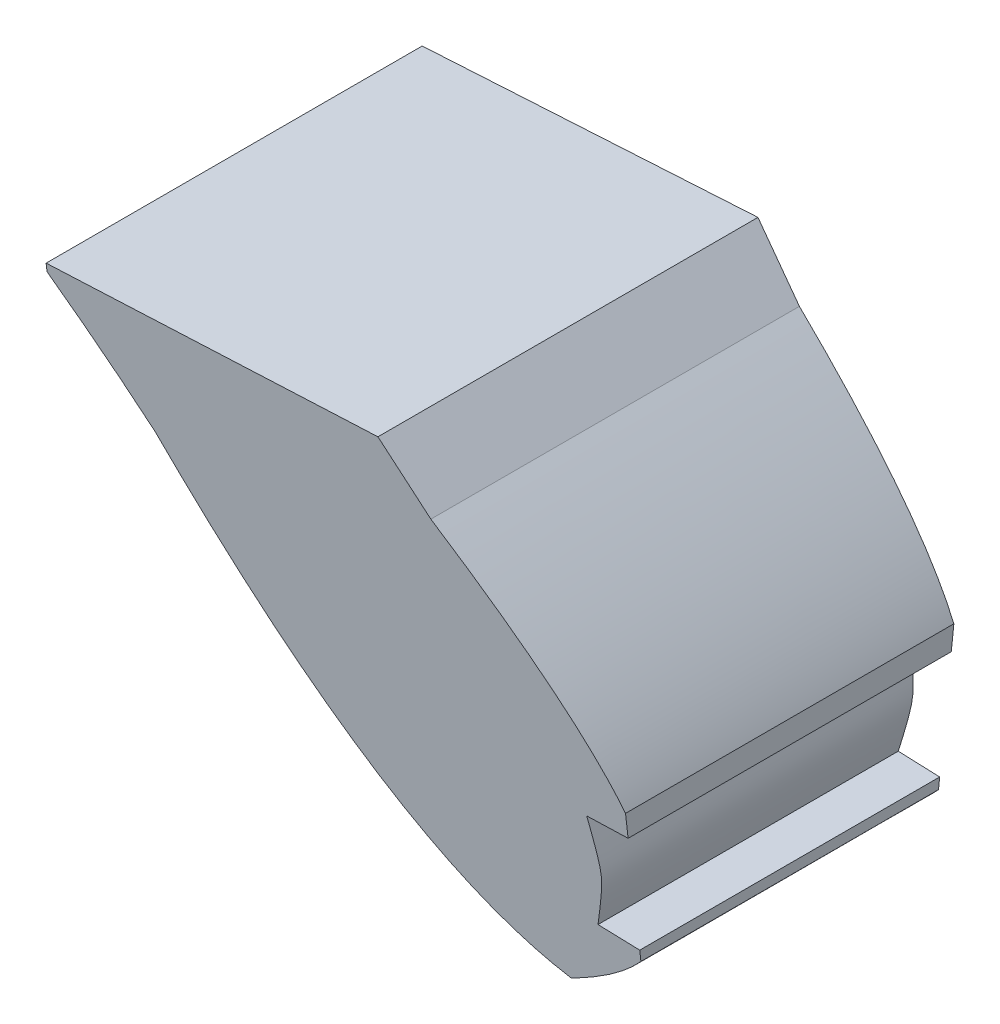
SolidWorks part; units mm, degrees
ref_plane "Alzado" through (0, 0, 0) normal (0, 0, 1) x (1, 0, 0)
ref_plane "Planta" through (0, 0, 0) normal (0, 1, 0) x (1, 0, 0)
ref_plane "Vista lateral" through (0, 0, 0) normal (1, 0, 0) x (0, 0, -1)
sketch "Croquis1" plane through (0, 0, 0) normal (0, 0, 1) x (1, 0, 0)
  line L0 (-8.9818, 12.6082) -> (-23.0359, 11.8716) construction
  line L1 (-8.9818, 12.6082) -> (-23.0359, 11.8716)
  line L2 (-8.9818, 12.6082) -> (-23.0359, 11.8716) construction
  line L4 (-8.9818, 12.6082) -> (-23.0359, 11.8716)
  line L6 (-1.3949, 1.9763) -> (0.3551, 2.2848) construction
  line L7 (-1.3949, 1.9763) -> (0.3551, 2.2848)
  line L8 (0.3551, 2.2848) -> (0.3551, 2.8423) construction
  line L9 (0.3551, 2.2848) -> (0.3551, 3.0015)
  line L10 (0.3551, -2.2848) -> (-1.3949, -2.2237) construction
  line L11 (0.3551, -2.2848) -> (-1.3949, -2.2237)
  line L12 (0.3551, 2.2848) -> (0.3551, -2.2848) construction
  line L13 (0.3551, -2.2848) -> (0.3551, -2.7233)
  line L14 (-8.9818, 12.6082) -> (-6.9949, 10.4774)
  line L15 (-23.0359, 11.5401) -> (-23.0359, 11.8716) construction
  line L16 (-23.0359, 11.5401) -> (-23.0359, 11.8716)
  arc A0 (-18.9452, 7.5409) -> (-23.0359, 11.5401) centre (-69.8841, -40.4718) ccw construction
  arc A1 (-18.9452, 7.5409) -> (-23.0359, 11.5401) centre (-69.8841, -40.4718) ccw
  spline S1 degree 2 poles (-1165.1036, 5893.6598) (818.9524, -5942.9252) (-471.5876, 5971.4584) knots 0.453698 0.453698 0.453698 0.546233 0.546233 0.546233 weights 1 1 1 only from (-18.9452, 7.5409) to (-2.8466, -5.0591) construction
  spline S2 degree 2 poles (-18.9452, 7.5409) (-10.215, -3.6976) (-2.8466, -5.0591) knots 0.497667 0.497667 0.497667 0.499554 0.499554 0.499554 weights 1 1 1
  spline S3 degree 2 poles (-5694.9897, 1886.3291) (5642.0208, -2053.6219) (-5584.6926, 2218.951) knots 0.453717 0.453717 0.453717 0.546322 0.546322 0.546322 weights 1 1 1 only from (0.3551, 3.0015) to (-6.9949, 10.4774) construction
  spline S4 degree 2 poles (0.3551, 3.0015) (-1.4487, 6.0584) (-6.9949, 10.4774) knots 0.500821 0.500821 0.500821 0.502013 0.502013 0.502013 weights 1 1 1
  spline S5 degree 2 poles (-1.3949, -2.2237) (-0.9075, -0.1237) (-1.3949, 1.9763) knots 0 0 0 1 1 1 weights 1 3.231801 1 construction
  spline S6 degree 2 poles (-1.3949, -2.2237) (-0.9075, -0.1237) (-1.3949, 1.9763) knots 0 0 0 1 1 1 weights 1 3.231801 1
  spline S7 degree 2 poles (-5992.358, 322.5754) (5976.1778, -523.0129) (-5953.8534, 722.2524) knots 0.453712 0.453712 0.453712 0.546274 0.546274 0.546274 weights 1 1 1 only from (-2.8466, -5.0591) to (0.3551, -2.7233) construction
  spline S8 degree 2 poles (-2.8466, -5.0591) (-0.7424, -3.9352) (0.3551, -2.7233) knots 0.498812 0.498812 0.498812 0.499413 0.499413 0.499413 weights 1 1 1
extrude "Saliente-Extruir1" add sketch "Croquis1" along normal mid plane 16 contours S2 S8 L13 L11 S6 L7 L9 S4 L14 L1 L16 A1
sketch "Croquis3" plane through (0, 0, 0) normal (0, 0, 1) x (1, 0, 0)
  line L0 (-6.742, 0) -> (0, 0) construction
  line L1 (-1.8181, 2) -> (-1.7771, 2.0103) construction
  line L3 (-1.8181, 2) -> (-0.1689, 2.4155) construction
  line L4 (-1.8181, 2) -> (0.3551, 3.0015)
  line L5 (0.3551, 3.0015) -> (0.3551, 0)
  line L6 (-1.9135, -2.1825) -> (0.3551, -2.2848)
  line L7 (0.3551, -2.2848) -> (0.3551, 0)
  parabola Q0 (-1.9135, -2.1825) -> (-1.8181, 2) focus (-3.3181, 0) apex (-1.3181, 0)
  dimension "D1" = 2
  dimension "D2" = 2
extrude "Cortar-Extruir1" [suppressed] cut sketch "Croquis3" against normal through all both and the other way through all
sketch "Croquis4" plane through (0, 0, 0) normal (0, 0, 1) x (1, 0, 0)
  line L0 (-1.3949, 1.9763) -> (0.3551, 2.2848) construction
  line L1 (-1.3949, 1.9763) -> (0.3551, 2.2848)
  line L2 (0.3551, 2.2848) -> (0.3551, 3.0015) construction
  line L3 (0.3551, 2.0374) -> (0.3551, 2.2848)
  line L4 (-1.3949, 1.9763) -> (0.3551, 2.0374)
  line L5 (0, 0) -> (-3.4665, 0) construction
  dimension "D1" = 2
extrude "Saliente-Extruir2" add sketch "Croquis4" along normal through all and the other way through all
sketch "Croquis7" plane through (0, 0, 0) normal (0, 0, 1) x (1, 0, 0)
  line L0 (0, 0) -> (-15.3945, 3.3171) construction
  line L1 (-17.3963, 18.9371) -> (-15.3945, 3.3171) construction
  line L2 (-15.3945, 3.3171) -> (-9.9316, -2.6296) construction
  line L3 (-15.3945, 3.3171) -> (-10.2385, 8.0535) construction
  line L4 (-17.3963, 18.9371) -> (-16.5429, 12.2783) construction
  line L5 (0, 0) -> (-1.3461, -2.2254) construction
  line L6 (-69.8841, 29.5282) -> (-81.9382, 42.5765) construction
  line L7 (-69.8841, 29.5282) -> (-20.9497, 29.5282) construction
  line L8 (-17.8101, 13.1658) -> (-25.5429, 13.1658)
  line L9 (-18.2059, 7.0951) -> (-21.9246, 11.9299) construction
  line L10 (0.3551, -2.5) -> (-2.4497, -2.0473)
  line L11 (-1.3461, -2.2254) -> (-2.0075, -3.6222) construction
  line L12 (-1.3461, -2.2254) -> (-1.4547, -2.8987) construction
  line L13 (-1.3461, -2.2254) -> (-1.2286, -1.4976) construction
  line L14 (0.3551, -2.2848) -> (0.3551, -2.7233) construction
  line L15 (0.3551, -2.2848) -> (-1.3949, -2.2237) construction
  line L16 (-2.0075, -3.6222) -> (-3.0629, -5.8512) construction
  line L17 (-2.6331, -4.9434) -> (-3.7044, -5.5324) construction
  line L18 (-2.6331, -4.9434) -> (-3.2248, -3.867) construction
  line L19 (-2.6331, -4.9434) -> (-2.2174, -6.1341) construction
  line L20 (-4.0838, -4.7637) -> (-1.6363, -5.0668) construction
  line L21 (-4.0838, -4.7637) -> (-0.036, -5.9454) construction
  line L22 (-4.0838, -4.7637) -> (-3.7621, -3.6616) construction
  line L23 (-4.0838, -4.7637) -> (-6.31, -3.7023) construction
  line L24 (-6.31, -3.7023) -> (-8.69, -2.5677) construction
  line L25 (-8.69, -2.5677) -> (-6.8421, -3.7725) construction
  line L26 (-8.69, -2.5677) -> (-7.9481, -1.4297) construction
  line L27 (-10.6884, -0.8477) -> (-8.69, -2.5677) construction
  line L28 (-10.6884, -0.8477) -> (-14.8546, 2.738) construction
  line L29 (-14.8546, 2.738) -> (-14.5337, 2.3989) construction
  line L30 (-14.8546, 2.738) -> (-14.6199, 2.9602) construction
  line L31 (-18.2059, 7.0951) -> (-14.8546, 2.738) construction
  line L32 (-8.9818, 12.6082) -> (-23.0359, 11.8716) construction
  line L33 (-8.9818, 12.6082) -> (-23.0359, 11.8716)
  line L34 (-21.9246, 11.9299) -> (-21.9826, 13.0367) construction
  line L35 (-21.9246, 11.9299) -> (-23.4156, 13.0367) construction
  arc A0 (-18.9452, 7.5409) -> (-23.0359, 11.5401) centre (-69.8841, -40.4718) ccw construction
  spline S0 degree 2 poles (-654.4568, 2937.5195) (409.3679, -2972.9237) (-163.476, 2987.5518) knots 0.467242 0.467242 0.467242 0.532662 0.532662 0.532662 weights 1 1 1 only from (-18.9452, 7.5409) to (-2.8466, -5.0591) construction
  spline S1 degree 2 poles (-18.6263, 7.1332) (-10.0803, -3.7225) (-2.8466, -5.0591) knots 0.497702 0.497702 0.497702 0.499554 0.499554 0.499554 weights 1 1 1 construction
  spline S3 degree 2 poles (-2999.4042, 119.7504) (2988.2948, -261.6206) (-2971.0465, 402.239) knots 0.467267 0.467267 0.467267 0.532713 0.532713 0.532713 weights 1 1 1 only from (-2.8466, -5.0591) to (0.3551, -2.7233) construction
  spline S4 degree 2 poles (-2.8466, -5.0591) (-2.7385, -5.0013) (-2.6331, -4.9434) knots 0.498812 0.498812 0.498812 0.498843 0.498843 0.498843 weights 1 1 1
  dimension "D1" = 2.5
  dimension "D2" = 22
  dimension "D3" = 16.17
  dimension "D4" = 54.138
  dimension "D5" = 34.566
  dimension "D6" = 50.413
sketch "Croquis6" plane through (0, 0, 0) normal (1, 0, 0) x (0, 0, -1)
  line L0 (8, 12.6082) -> (8, 10.4774) construction
  line L1 (8, 12.6082) -> (8, -5.0591)
  line L2 (-8, 12.6082) -> (-8, 10.4774) construction
  line L3 (-8, 12.6082) -> (-8, -5.0591)
  line L4 (-8, -5.0591) -> (8, -5.0591) construction
  line L5 (-8, -5.0591) -> (-6, -5.0591)
  line L6 (8, 12.6082) -> (6, -5.0591)
  line L7 (-8, 12.6082) -> (-6, -5.0591)
  line L8 (6, -5.0591) -> (8, -5.0591)
  dimension "D1" = 2
  dimension "D2" = 2
extrude "Cortar-Extruir2" cut sketch "Croquis6" against normal through all and the other way through all
